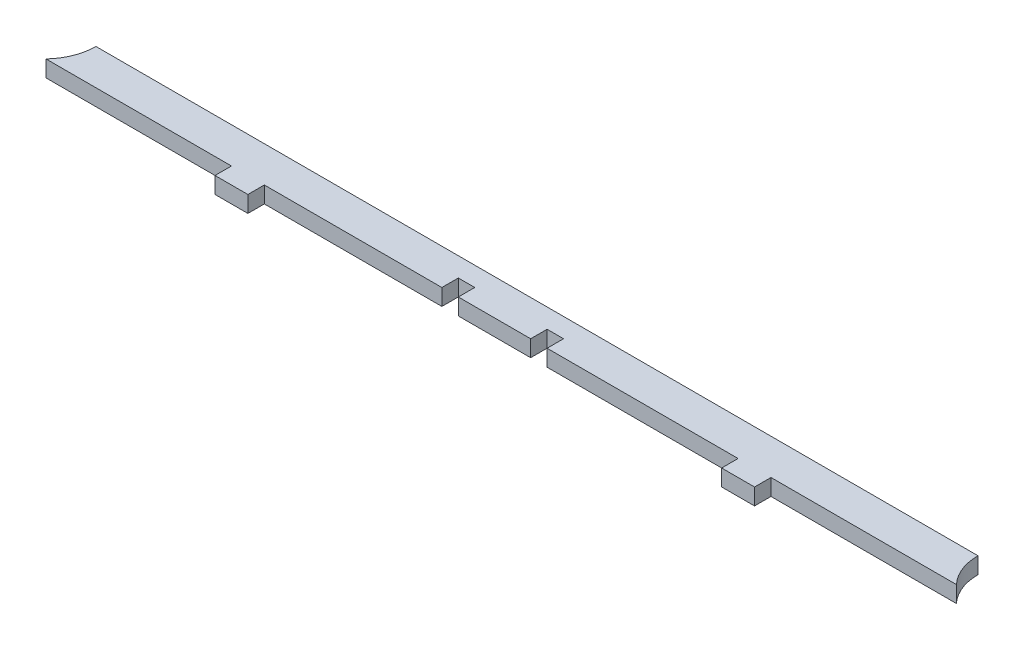
SolidWorks part; units mm, degrees
ref_plane "Front Plane" through (0, 0, 0) normal (1, 0, 0) x (0, 1, 0)
ref_plane "Top Plane" through (0, 0, 0) normal (0, 0, 1) x (0, 1, 0)
ref_plane "Right Plane" through (0, 0, 0) normal (0, 1, 0) x (-1, 0, 0)
sketch "Sketch1" plane through (0, 0, 0) normal (0, 1, 0) x (-1, 0, 0)
  line L0 (-150, 0) -> (150, 0) construction
  line L1 (-150, 15.875) -> (-130, 15.875) construction
  line L2 (-130, 15.875) -> (-130, 10.875) construction
  line L3 (-134.125, 0) -> (134.125, 0)
  line L4 (-138.435, 10.875) -> (138.435, 10.875)
  line L5 (0, 10.875) -> (27.04, 10.875) construction
  line L6 (17.04, 10.875) -> (27.04, 10.875)
  line L7 (27.04, 10.875) -> (17.04, 10.875)
  line L8 (27.04, 10.875) -> (27.04, 15.875)
  line L9 (27.04, 15.875) -> (17.04, 15.875)
  line L10 (17.04, 10.875) -> (17.04, 15.875)
  line L11 (22.04, 10.875) -> (72.04, 10.875) construction
  line L12 (22.04, 15.875) -> (22.04, 10.875) construction
  line L13 (22.04, 10.875) -> (-72.04, 10.875)
  line L14 (72.04, 10.875) -> (82.04, 10.875)
  line L15 (72.04, 10.875) -> (72.04, 15.875)
  line L16 (72.04, 15.875) -> (82.04, 15.875)
  line L17 (82.04, 10.875) -> (82.04, 15.875)
  line L19 (-72.04, 10.875) -> (-82.04, 10.875)
  line L20 (-72.04, 10.875) -> (-72.04, 15.875)
  line L21 (-72.04, 15.875) -> (-82.04, 15.875)
  line L22 (-82.04, 10.875) -> (-82.04, 15.875)
  arc A0 (-134.125, 0) -> (-138.435, 10.875) centre (-150, 0) ccw
  arc A1 (138.435, 10.875) -> (134.125, 0) centre (150, 0) ccw
  point P4 (0, 0)
  dimension "D2" = 31.75
  dimension "D5" = 27.04
  dimension "D1" = 300
  dimension "D3" = 5
  dimension "D4" = 20
  dimension "D6" = 10
  dimension "D7" = 5
  dimension "D8" = 50
  dimension "D9" = 94.08
extrude "Boss-Extrude1" add sketch "Sketch1" along normal mid plane 5 contours A1 L4 A0 L3 | L22 L4 L20 L21 | L4 L17 L16 L15
sketch "Sketch2" plane through (0, 2.5, 0) normal (0, 1, 0) x (-1, 0, 0)
  line L2 (-134.125, 0) -> (134.125, 0) construction
  line L11 (-13.955, 0) -> (-13.955, 10.875) construction
  line L12 (-72.04, 10.875) -> (72.04, 10.875) construction
  line L13 (-13.955, 10.875) -> (-13.955, 5.875)
  line L14 (-13.955, 5.875) -> (-8.955, 5.875)
  line L15 (-8.955, 5.875) -> (-8.955, 10.875)
  line L16 (-13.955, 10.875) -> (-8.955, 10.875)
  line L17 (-13.955, 10.875) -> (18.045, 10.875) construction
  line L18 (18.045, 10.875) -> (18.045, 5.875)
  line L19 (18.045, 5.875) -> (13.045, 5.875)
  line L20 (13.045, 5.875) -> (13.045, 10.875)
  line L21 (13.045, 10.875) -> (18.045, 10.875)
  point P14 (-13.955, 10.875)
  dimension "D1" = 120.39
  dimension "D2" = 32
  dimension "D3" = 5
  dimension "D4" = 5
extrude "Cut-Extrude2" cut sketch "Sketch2" against normal up to next contours L15 L16 L13 L14 | L20 L21 L18 L19
